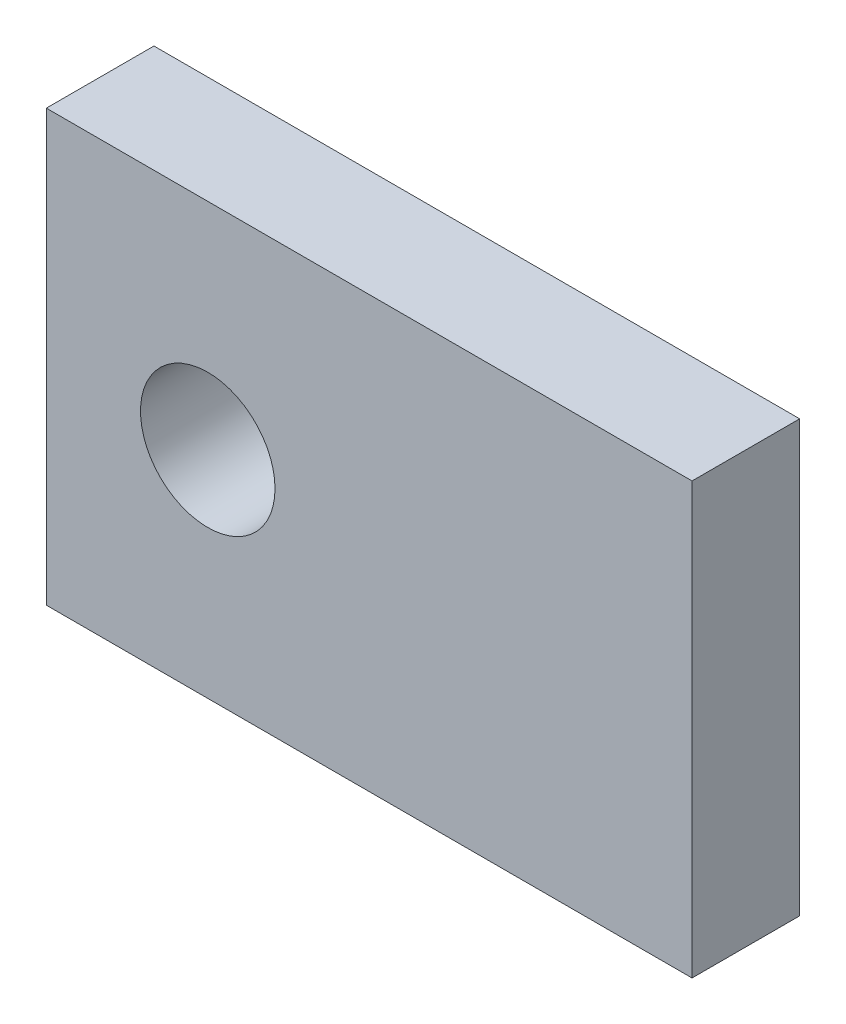
SolidWorks part; units mm, degrees
material "Balsa"
ref_plane "Front Plane" through (0, 0, 0) normal (0, 0, 1) x (1, 0, 0)
ref_plane "Top Plane" through (0, 0, 0) normal (0, 1, 0) x (1, 0, 0)
ref_plane "Right Plane" through (0, 0, 0) normal (1, 0, 0) x (0, 0, -1)
sketch "Sketch1" plane through (0, 0, 0) normal (0, 0, 1) x (1, 0, 0)
  line L1 (-19.05, 12.7) -> (19.05, 12.7)
  line L2 (-19.05, 12.7) -> (-19.05, -12.7)
  line L3 (-19.05, -12.7) -> (19.05, -12.7)
  line L4 (19.05, 12.7) -> (19.05, -12.7)
  line L5 (-19.05, 12.7) -> (19.05, -12.7) construction
  line L6 (-19.05, -12.7) -> (19.05, 12.7) construction
  point P0 (0, 0)
  dimension "D1" = 25.4
  dimension "1.5" = 38.1
extrude "Boss-Extrude1" add sketch "Sketch1" along normal blind 6.35
sketch "Sketch2" plane through (0, 0, 6.35) normal (0, 0, 1) x (1, 0, 0)
  line L0 (0, 12.7) -> (0, -12.7) construction
  line L1 (19.05, 12.7) -> (-19.05, 12.7) construction
  line L2 (-19.05, -12.7) -> (19.05, -12.7) construction
  line L3 (0, 0) -> (-19.05, 0) construction
  line L6 (-19.05, 12.7) -> (-19.05, -12.7) construction
  circle A0 centre (-9.525, 0) radius 3.9688
  point P10 (-12.7, 0)
  dimension "D1" = 7.9375
extrude "Cut-Extrude1" cut sketch "Sketch2" against normal through all
